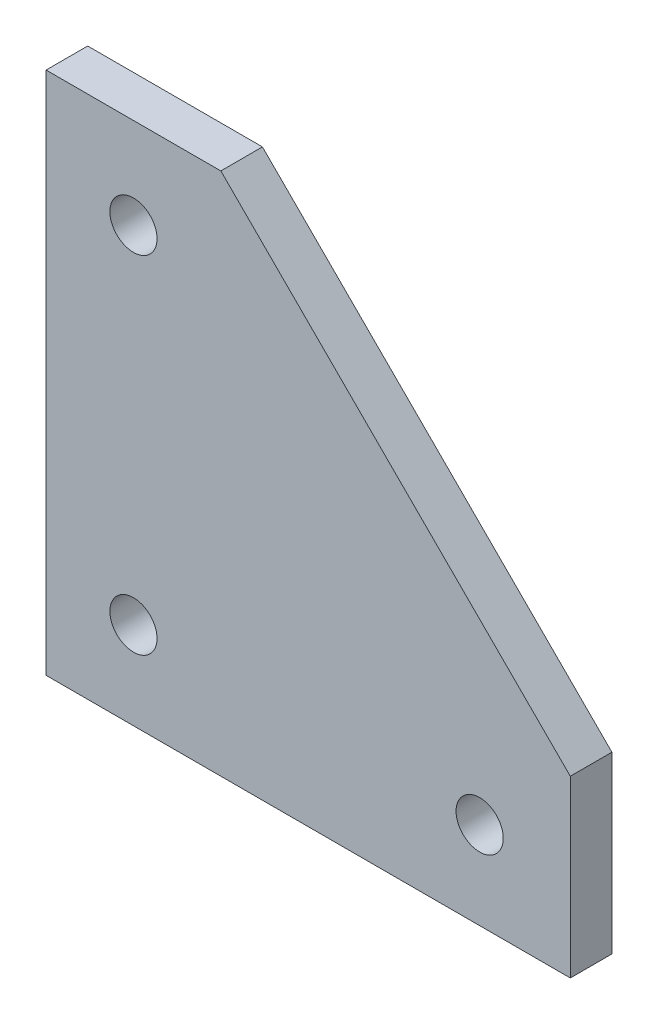
SolidWorks part; units mm, degrees
material "PE High Density"
ref_plane "Front Plane" through (0, 0, 0) normal (0, 0, 1) x (1, 0, 0)
ref_plane "Top Plane" through (0, 0, 0) normal (0, 1, 0) x (1, 0, 0)
ref_plane "Right Plane" through (0, 0, 0) normal (1, 0, 0) x (0, 0, -1)
sketch "Sketch1" plane through (0, 0, 0) normal (0, 0, 1) x (1, 0, 0)
  line L0 (0, 0) -> (0, 60)
  line L1 (10, 10) -> (49.624, 10) construction
  line L3 (10, 10) -> (10, 49.624) construction
  line L4 (60, 20) -> (20, 60)
  line L5 (60, 0) -> (0, 0)
  line L7 (60, 20) -> (60, 0)
  line L8 (0, 60) -> (20, 60)
  circle A0 centre (10, 10) radius 2.7
  circle A2 centre (49.624, 10) radius 2.7
  circle A4 centre (10, 49.624) radius 2.7
  point P1 (0, 0)
  point P5 (9.015, 49.624)
  point P8 (0, 0)
  point P12 (60, 10)
  point P17 (10, 60)
  dimension "D1" = 60
  dimension "D2" = 20
  dimension "D3" = 5.4
  dimension "D4" = 39.624
extrude "Boss-Extrude1" add sketch "Sketch1" along normal mid plane 4.7625
